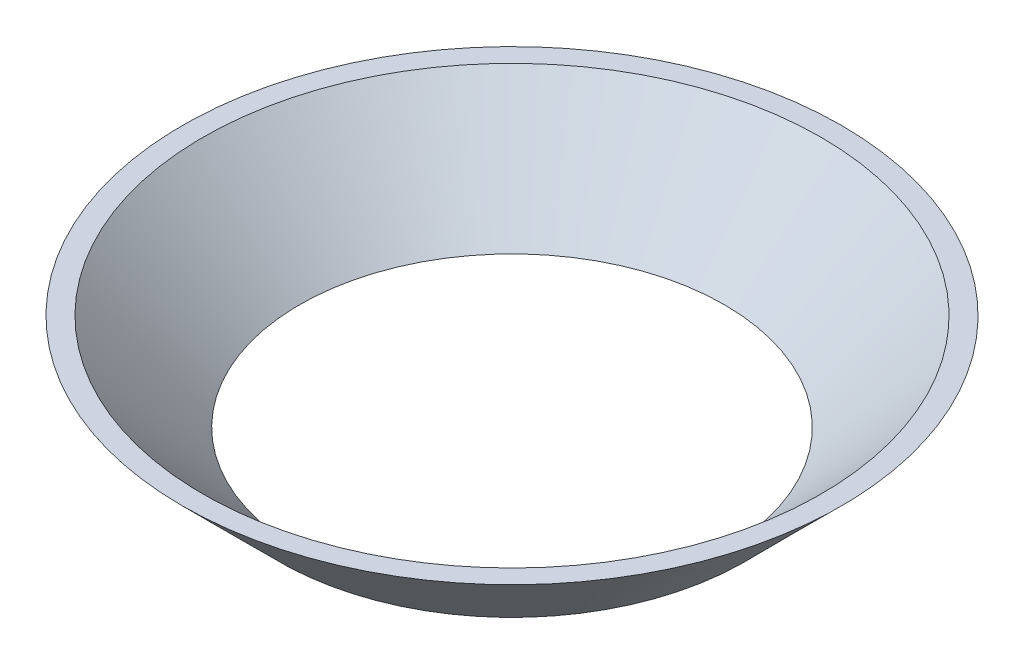
SolidWorks part; units mm, degrees
ref_plane "Plan de face" through (0, 0, 0) normal (0, 0, 1) x (1, 0, 0)
ref_plane "Plan de dessus" through (0, 0, 0) normal (0, 1, 0) x (1, 0, 0)
ref_plane "Plan de droite" through (0, 0, 0) normal (1, 0, 0) x (0, 0, -1)
sketch "Esquisse1" plane through (0, 0, 0) normal (0, 0, 1) x (1, 0, 0)
  line L0 (0, 0) -> (0, 8.495) construction
  line L1 (31.8, 0) -> (45, 13.2)
  line L2 (45, 13.2) -> (42.2, 13.2)
  line L3 (42.2, 13.2) -> (29, 0)
  line L4 (29, 0) -> (31.8, 0)
  line L5 (0, 0) -> (29, 0) construction
  dimension "D1" = 90
  dimension "D2" = 58
  dimension "D3" = 45
  dimension "D4" = 2.8
revolve "Révolution1" add sketch "Esquisse1" angle 360 about L0
